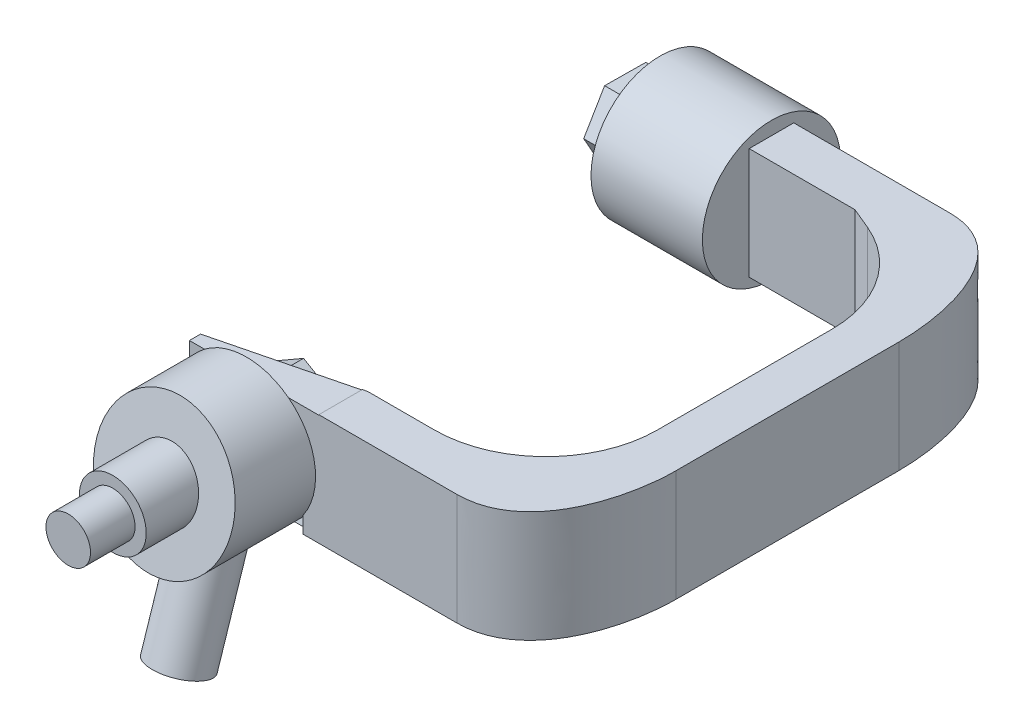
SolidWorks part; units mm, degrees
ref_plane "Front Plane" through (0, 0, 0) normal (0, 0, 1) x (1, 0, 0)
ref_plane "Top Plane" through (0, 0, 0) normal (0, 1, 0) x (1, 0, 0)
ref_plane "Right Plane" through (0, 0, 0) normal (1, 0, 0) x (0, 0, -1)
sketch "Sketch1" plane through (0, 0, 0) normal (0, 1, 0) x (1, 0, 0)
  line L0 (0, 0) -> (76.2, 0)
  line L1 (76.2, 0) -> (101.6, 0)
  line L2 (228.6, 127) -> (228.6, 326.1152)
  line L3 (3.1176, 457.1894) -> (123.7407, 457.1894)
  line L4 (123.7407, 457.1894) -> (147.939, 447.1067)
  line L5 (0, 0) -> (0, -50.8)
  line L6 (0, -50.8) -> (127, -50.8)
  line L7 (127, -50.8) -> (177.8, -50.8)
  line L8 (3.1176, 457.1894) -> (3.1176, 507.9894)
  line L9 (3.1176, 507.9894) -> (130.1176, 507.9894)
  line L10 (130.1176, 507.9894) -> (180.9176, 507.9894)
  line L11 (279.4, 351.5152) -> (279.4, 97.5152)
  arc A0 (101.6, 0) -> (228.6, 127) centre (101.6, 127) ccw
  arc A1 (147.939, 447.1067) -> (228.6, 326.1152) centre (97.5259, 326.1152) cw
  spline S0 degree 3 poles (180.9176, 507.9894) (258.0968, 507.9894) (279.4, 408.3661) (279.4, 351.5152) knots 0 0 0 0 0.284384 0.284384 0.284384 0.284384
  spline S1 degree 3 poles (279.4, 97.5152) (279.4, 39.9495) (253.6127, -50.8) (177.8, -50.8) knots 0.713424 0.713424 0.713424 0.713424 1 1 1 1
  dimension "D1" = 50.8
  dimension "D4" = 127
  dimension "D7" = 50.8
  dimension "D9" = 50.8
  dimension "D10" = 25.4
  dimension "D2" = 457.2
  dimension "D3" = 50.8
  dimension "D5" = 127
  dimension "D6" = 50.8
  dimension "D8" = 254
extrude "Boss-Extrude1" add sketch "Sketch1" along normal blind 127
sketch "Sketch2" plane through (3.1176, 0, 0) normal (-1, 0, 0) x (0, 0, 1)
  circle A0 centre (-482.5894, 63.5) radius 78.74
  dimension "D1" = 157.48
extrude "Boss-Extrude2" add sketch "Sketch2" along normal blind 127
sketch "Sketch3" plane through (-123.8824, 0, 0) normal (-1, 0, 0) x (0, 0, 1)
  line L1 (-435.6647, 63.9705) -> (-459.5345, 104.3732)
  line L2 (-459.5345, 104.3732) -> (-506.4592, 103.9027)
  line L3 (-506.4592, 103.9027) -> (-529.514, 63.0295)
  line L4 (-529.514, 63.0295) -> (-505.6442, 22.6268)
  line L5 (-505.6442, 22.6268) -> (-458.7195, 23.0973)
  line L6 (-458.7195, 23.0973) -> (-435.6647, 63.9705)
  circle A0 centre (-482.5894, 63.5) radius 40.64 construction
  dimension "D1" = 81.28
extrude "Boss-Extrude3" add sketch "Sketch3" along normal blind 40.132
sketch "Sketch4" plane through (0, 0, 0) normal (-1, 0, 0) x (0, 0, 1)
  line L1 (50.8, 127) -> (0, 127)
  line L2 (50.8, 127) -> (50.8, 0)
  line L3 (50.8, 0) -> (0, 0)
  line L4 (0, 127) -> (0, 0)
extrude "Boss-Extrude4" add sketch "Sketch4" along normal blind 127
sketch "Sketch5" plane through (0, 0, 0) normal (0, -1, 0) x (-1, 0, 0)
  line L0 (127, -38.1) -> (127, 0)
  line L2 (127, 0) -> (127, -50.8) construction
  line L3 (127, 0) -> (-25.4, 0)
  line L4 (-101.6, 0) -> (127, 0) construction
  line L5 (-25.4, 0) -> (127, -38.1)
  dimension "D1" = 38.1
  dimension "D2" = 152.4
extrude "Cut-Extrude1" cut sketch "Sketch5" against normal through all
sketch "Sketch7" plane through (0, 0, 50.8) normal (0, 0, 1) x (1, 0, 0)
  line L0 (-127, 0) -> (-127, 127) construction
  line L1 (-60.3824, 110.427) -> (-101.0224, 86.9635)
  line L2 (-101.0224, 86.9635) -> (-101.0224, 40.0365)
  line L3 (-101.0224, 40.0365) -> (-60.3824, 16.573)
  line L4 (-60.3824, 16.573) -> (-19.7424, 40.0365)
  line L5 (-19.7424, 40.0365) -> (-19.7424, 86.9635)
  line L6 (-19.7424, 86.9635) -> (-60.3824, 110.427)
  circle A0 centre (-60.3824, 63.5) radius 40.64 construction
  point P11 (-127, 63.5)
  dimension "D1" = 81.28
  dimension "D2" = 0
extrude "Boss-Extrude6" add sketch "Sketch7" against normal blind 63.5
sketch "Sketch9" plane through (0, 0, 50.8) normal (0, 0, 1) x (1, 0, 0)
  line L0 (-127, 0) -> (-127, 127) construction
  line L1 (-61.9412, 110.427) -> (-102.5812, 86.9635)
  line L2 (-102.5812, 86.9635) -> (-102.5812, 40.0365)
  line L3 (-102.5812, 40.0365) -> (-61.9412, 16.573)
  line L4 (-61.9412, 16.573) -> (-21.3012, 40.0365)
  line L5 (-21.3012, 40.0365) -> (-21.3012, 86.9635)
  line L6 (-21.3012, 86.9635) -> (-61.9412, 110.427)
  circle A0 centre (-61.9412, 63.5) radius 40.64 construction
  point P10 (-127, 63.5)
  dimension "D1" = 81.28
  dimension "D2" = 0
extrude "Boss-Extrude7" add sketch "Sketch9" along normal blind 0.254
sketch "Sketch10" plane through (0, 0, 50.8) normal (0, 0, 1) x (1, 0, 0)
  circle A0 centre (-61.9412, 63.9705) radius 78.74
  dimension "D1" = 157.48
extrude "Boss-Extrude8" add sketch "Sketch10" along normal blind 127
ref_plane "Plane1" through (-139.7, 0, 0) normal (1, 0, 0) x (0, 0, -1)
sketch "Sketch11" plane through (-139.7, 0, 0) normal (1, 0, 0) x (0, 0, -1)
  line L2 (-201.1457, -18.2304) -> (-201.1457, 206.9054)
  line L7 (-201.1457, 206.9054) -> (-111.7778, 206.9054)
  line L8 (-111.7778, 206.9054) -> (-201.1457, -183.516)
  line L9 (-201.1457, -183.516) -> (-201.1457, -18.2304)
  dimension "D2" = 225.1358
extrude "Cut-Extrude4" cut sketch "Sketch11" along normal mid plane 2540
sketch "Sketch12" plane through (0, 0, 50.8) normal (0, 0, 1) x (1, 0, 0)
  circle A0 centre (-61.9412, 63.9705) radius 38.1
  dimension "D1" = 76.2
extrude "Boss-Extrude9" add sketch "Sketch12" along normal blind 152.4
sketch "Sketch13" plane through (0, 0, 203.2) normal (0, 0, 1) x (1, 0, 0)
  circle A0 centre (-61.9412, 63.9705) radius 25.4
  dimension "D1" = 50.8
extrude "Boss-Extrude10" add sketch "Sketch13" along normal blind 50.8
sketch "Sketch18" plane through (0, 0, 0) normal (1, 0, 0) x (0, 0, -1)
  line L18 (-50.8, -14.7695) -> (-90.1689, -135.5134)
  line L19 (-90.1689, -135.5134) -> (-162.6152, -111.892)
  line L20 (-50.8, -14.7695) -> (-123.2463, 8.8519)
  line L23 (-123.2463, 8.8519) -> (-162.6152, -111.892)
  dimension "D2" = 76.2
  dimension "D1" = 76.2
  dimension "D3" = 127
extrude "Boss-Extrude11" add sketch "Sketch18" against normal blind 127
sketch "Sketch24" plane through (0, 127, 0) normal (0, 1, 0) x (1, 0, 0)
  line L0 (20.493, -50.8) -> (20.493, -1.2267)
  line L1 (-14.7472, -50.8) -> (177.8, -50.8) construction
  line L2 (-127, -38.1) -> (25.4, 0) construction
  line L3 (20.493, -1.2267) -> (-127, -38.1)
  line L4 (-127, -38.1) -> (-127, -50.8)
  line L5 (-127, -50.8) -> (20.493, -50.8)
extrude "Cut-Extrude16" cut sketch "Sketch24" against normal blind 0.508
sketch "Sketch25" plane through (0, -149.0659, 48.6034) normal (0, -0.9507, 0.31) x (1, 0, 0)
  line L0 (-127, 119.9192) -> (-127, 43.7192) construction
  line L2 (-127, 119.9192) -> (0, 119.9192) construction
  line L3 (-127, 43.7192) -> (0, 43.7192) construction
  line L12 (2.54, 41.1792) -> (2.54, 122.4592)
  line L13 (2.54, 122.4592) -> (-129.54, 122.4592)
  line L14 (-129.54, 122.4592) -> (-129.54, 41.1792)
  line L15 (-129.54, 41.1792) -> (2.54, 41.1792)
  line L16 (2.54, 41.1792) -> (2.54, 122.4592)
  line L17 (2.54, 122.4592) -> (-129.54, 122.4592)
  line L18 (-129.54, 122.4592) -> (-129.54, 41.1792)
  line L19 (-129.54, 41.1792) -> (2.54, 41.1792)
  circle A0 centre (-63.5, 81.8192) radius 31.75
  point P2 (0, 0)
  dimension "D1" = 63.5
  dimension "D2" = 63.5
  dimension "D3" = 38.1
  dimension "D4" = 38.1
  dimension "D5" = 2.54
extrude "Cut-Extrude17" cut sketch "Sketch25" against normal up to surface (124.9458 mm away)
sketch "Sketch26" plane through (0, -149.0659, 48.6034) normal (0, -0.9507, 0.31) x (1, 0, 0)
  circle A0 centre (-63.5, 81.8192) radius 25.4
  dimension "D1" = 50.8
extrude "Cut-Extrude18" cut sketch "Sketch26" against normal blind 76.2
